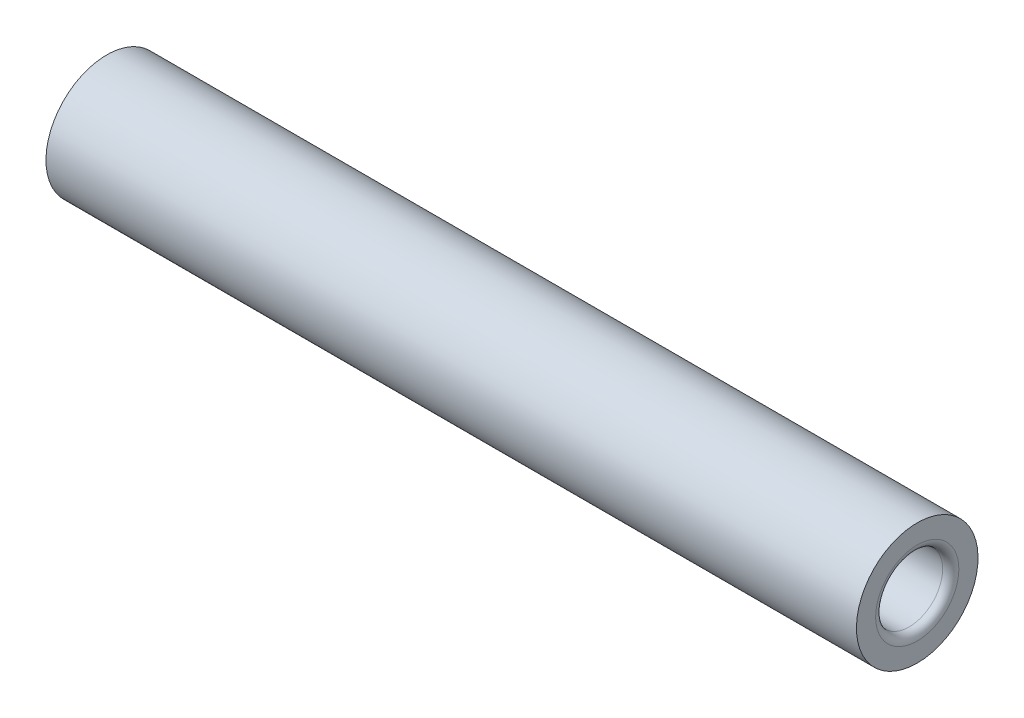
SolidWorks part; units mm, degrees
ref_plane "Front Plane" through (0, 0, 0) normal (0, 0, 1) x (1, 0, 0)
ref_plane "Top Plane" through (0, 0, 0) normal (0, 1, 0) x (1, 0, 0)
ref_plane "Right Plane" through (0, 0, 0) normal (1, 0, 0) x (0, 0, -1)
sketch "Sketch1" plane through (0, 0, 0) normal (0, 0, 1) x (1, 0, 0)
  line L1 (0, 0) -> (50.8, 0) construction
  line L2 (0, 0) -> (0, 3.81)
  line L3 (0, 3.81) -> (50.8, 3.81)
  line L4 (50.8, 0) -> (50.8, 3.81)
  line L5 (25.4, 3.81) -> (25.4, 0) construction
  line L7 (12.9075, 0) -> (0, 0)
  line L8 (37.8925, 0) -> (50.8, 0)
  line L11 (12.9075, 0) -> (37.8925, 0)
  point P208 (25.4, 1.5)
  dimension "D1" = 50.8
  dimension "D2" = 3.81
revolve "Revolve1" add sketch "Sketch1" angle 360 about L3
sketch "Sketch4" plane through (0, 0, 0) normal (-1, 0, 0) x (0, 0, 1)
  point P0 (0, 3.81)
hole_wizard "Tap Drill for M4 Helicoil1" positions "Sketch5" profile "Sketch6" hole size "M4x0.7" standard "ANSI Metric"
sketch "Sketch5" plane through (0, 0, 0) normal (-1, 0, 0) x (0, 0, 1)
  point P0 (0, 3.81)
sketch "Sketch6" plane through (0, 3.81, 0) normal (0, 1, 0) x (0, 0, 1)
  line L0 (0, 0) -> (0, 10.1518)
  line L1 (0, 10.1518) -> (2.1, 8.89)
  line L2 (2.1, 8.89) -> (2.1, 0)
  line L5 (2.1, 0) -> (0, 0)
  line L10 (0, 10.1518) -> (-2.1, 8.89) construction
  line L11 (0, -6.35) -> (0, 107.95) construction
  dimension "Hole Dia." = 4.2
  dimension "Hole Depth" = 8.89
  dimension "Drill Angle" = 118
ref_plane "Plane1" through (25.4, 0, 0) normal (-1, 0, 0) x (0, 0, 1)
mirror "Mirror1" about plane through (25.4, 0, 0) normal (-1, 0, 0) of "Tap Drill for M4 Helicoil1"
fillet "Fillet1" radius 0.508 2 edges at (0, 3.81, 2.1) (50.8, 3.81, -2.1)
equation "\"arm spacing\"= 2"
equation "\"D1@Sketch1\"=\"arm spacing\""
equation "\"D2@Sketch1\"=\"roller diameter\"/2"
equation "\"symbol room\"= ( ( 35 / 2 ) - 6.5 )"
equation "\"roller diameter\"= .3"
